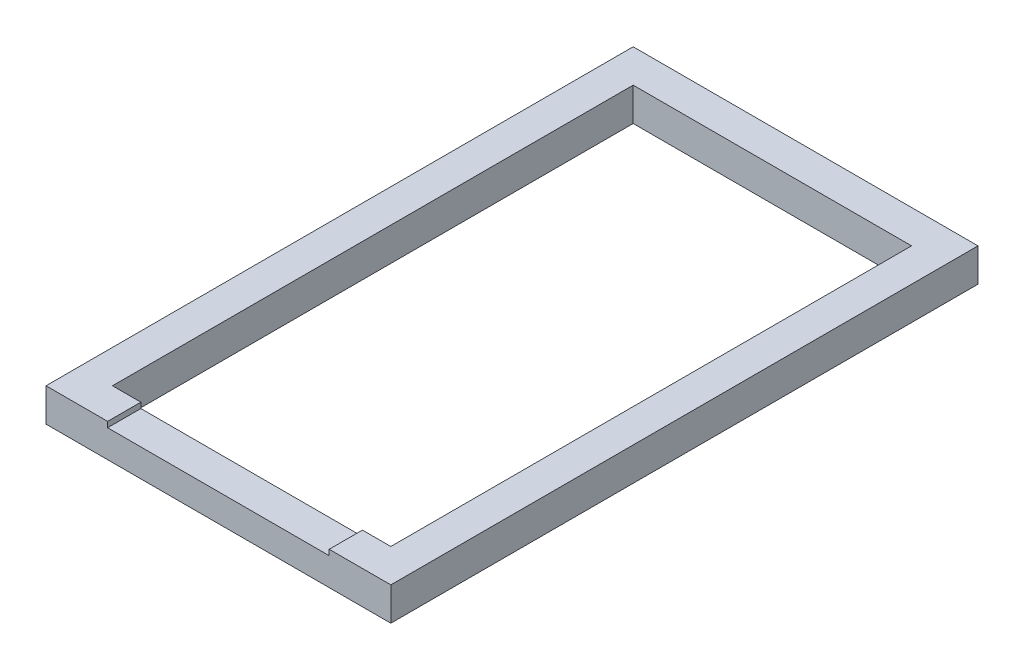
SolidWorks part; units mm, degrees
material "Бетон М200"
ref_plane "Спереди" through (0, 0, 0) normal (0, 0, 1) x (1, 0, 0)
ref_plane "Сверху" through (0, 0, 0) normal (0, 1, 0) x (1, 0, 0)
ref_plane "Справа" through (0, 0, 0) normal (1, 0, 0) x (0, 0, -1)
sketch "Эскиз1" plane through (0, 0, 0) normal (0, 1, 0) x (1, 0, 0)
  line L0 (-3112.5, -5300) -> (3112.5, -5300)
  line L1 (-2812.5, 5000) -> (2812.5, 5000) construction
  line L2 (-2812.5, 5000) -> (-2812.5, -5000) construction
  line L3 (-2812.5, -5000) -> (2812.5, -5000) construction
  line L4 (2812.5, 5000) -> (2812.5, -5000) construction
  line L5 (3112.5, 5300) -> (3112.5, -5300)
  line L6 (-3112.5, 5300) -> (3112.5, 5300)
  line L7 (-3112.5, 5300) -> (-3112.5, -5300)
  line L8 (2512.5, 4700) -> (2512.5, -4700)
  line L9 (-2512.5, -4700) -> (2512.5, -4700)
  line L10 (-2512.5, 4700) -> (-2512.5, -4700)
  line L11 (-2512.5, 4700) -> (2512.5, 4700)
  dimension "D1" = 300
  dimension "D2" = 300
extrude "Бобышка-Вытянуть1" add sketch "Эскиз1" against normal blind 600
sketch "Эскиз2" plane through (0, 0, 5300) normal (0, 0, 1) x (1, 0, 0)
  line L0 (-3112.5, 0) -> (3112.5, 0) construction
  line L1 (-2000, 0) -> (2000, 0)
  line L2 (-2000, 0) -> (-2000, -100)
  line L3 (-2000, -100) -> (2000, -100)
  line L4 (2000, 0) -> (2000, -100)
  line L5 (-2000, 0) -> (-2000, 16) construction
  point P6 (0, 0)
  dimension "D1" = 100
extrude "Вырез-Вытянуть2" cut sketch "Эскиз2" against normal up to surface (600 mm away) from surface at 0 up to face at (0, -300, 4700) starting at face at (0, -300, 5300)
